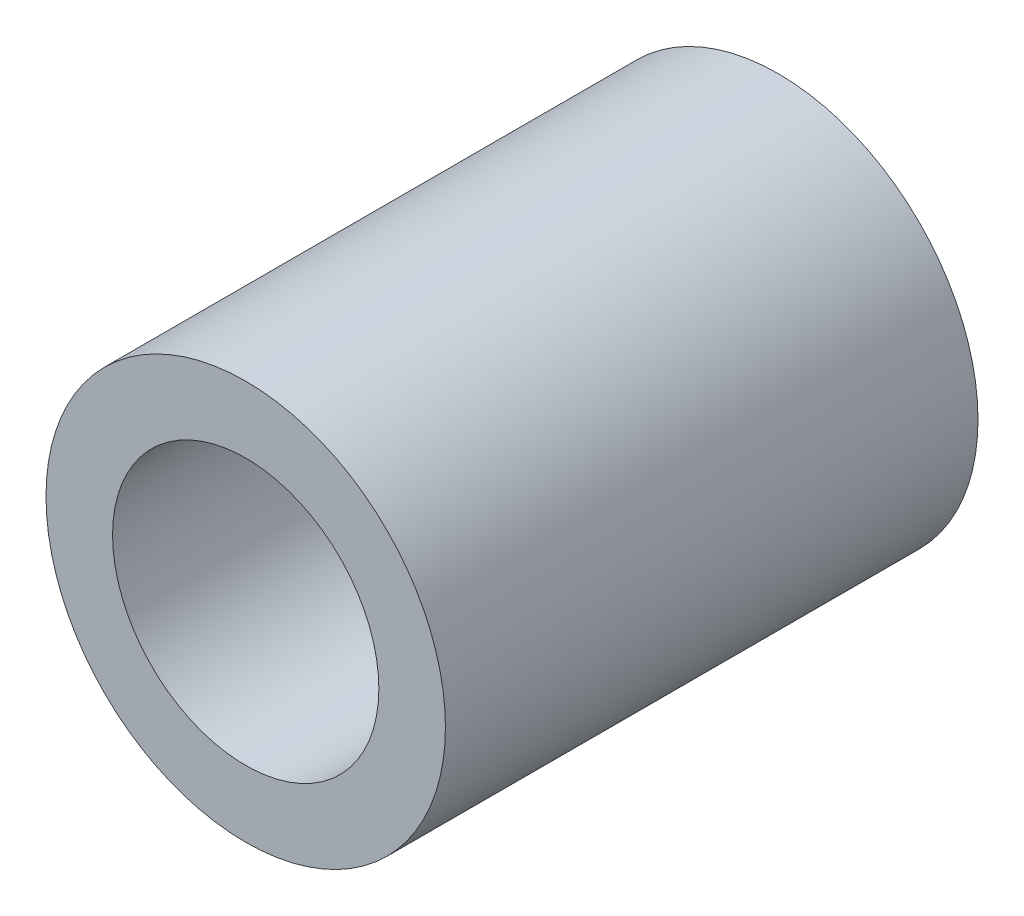
SolidWorks part; units mm, degrees
ref_plane "Plan de face" through (0, 0, 0) normal (0, 0, 1) x (1, 0, 0)
ref_plane "Plan de dessus" through (0, 0, 0) normal (0, 1, 0) x (1, 0, 0)
ref_plane "Plan de droite" through (0, 0, 0) normal (1, 0, 0) x (0, 0, -1)
sketch "Esquisse1" plane through (0, 0, 0) normal (0, 0, 1) x (1, 0, 0)
  circle A0 centre (0, 0) radius 19.05
extrude "Boss.-Extru.1" add sketch "Esquisse1" along normal blind 50.8
sketch "Esquisse4" plane through (0, 0, 50.8) normal (0, 0, 1) x (1, 0, 0)
  circle A0 centre (0, 0) radius 12.7
extrude "Enlèv. mat.-Extru.1" cut sketch "Esquisse4" against normal blind 43.45
sketch "Esquisse5" plane through (0, 0, 0) normal (0, 0, -1) x (-1, 0, 0)
  circle A0 centre (0, 0) radius 6.35
extrude "Enlèv. mat.-Extru.3" cut sketch "Esquisse5" against normal blind 7.35
